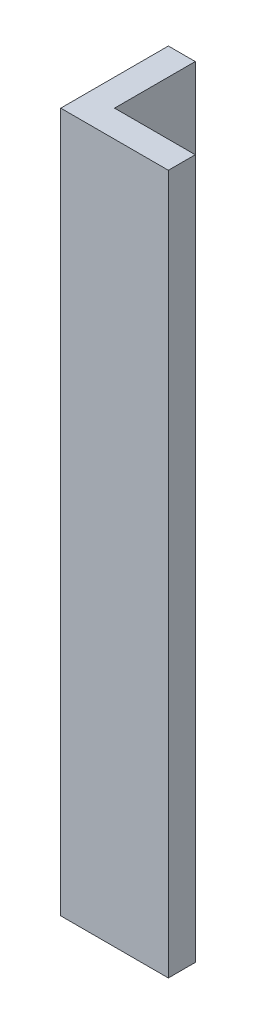
SolidWorks part; units mm, degrees
ref_plane "Front Plane" through (0, 0, 0) normal (0, 0, 1) x (1, 0, 0)
ref_plane "Top Plane" through (0, 0, 0) normal (0, 1, 0) x (1, 0, 0)
ref_plane "Right Plane" through (0, 0, 0) normal (1, 0, 0) x (0, 0, -1)
sketch "Sketch1" plane through (0, 0, 0) normal (0, 1, 0) x (1, 0, 0)
  line L1 (-16.9032, 9.3548) -> (-11.9032, 9.3548)
  line L2 (-16.9032, 9.3548) -> (-16.9032, -10.6452)
  line L3 (-16.9032, -10.6452) -> (-8.5806, -10.6452)
  line L4 (-11.9032, 9.3548) -> (-11.9032, -5.6452)
  line L5 (-11.9032, -5.6452) -> (3.0968, -5.6452)
  line L6 (-16.9032, -4.6452) -> (-16.9032, -10.6452)
  line L7 (-16.9032, -10.6452) -> (3.0968, -10.6452)
  line L8 (3.0968, -5.6452) -> (3.0968, -10.6452)
  dimension "D1" = 20
  dimension "D2" = 20
  dimension "D3" = 5
  dimension "D4" = 5
extrude "Boss-Extrude1" add sketch "Sketch1" along normal blind 130 contours L8 L5 L4 L1 L2 L3 L7
